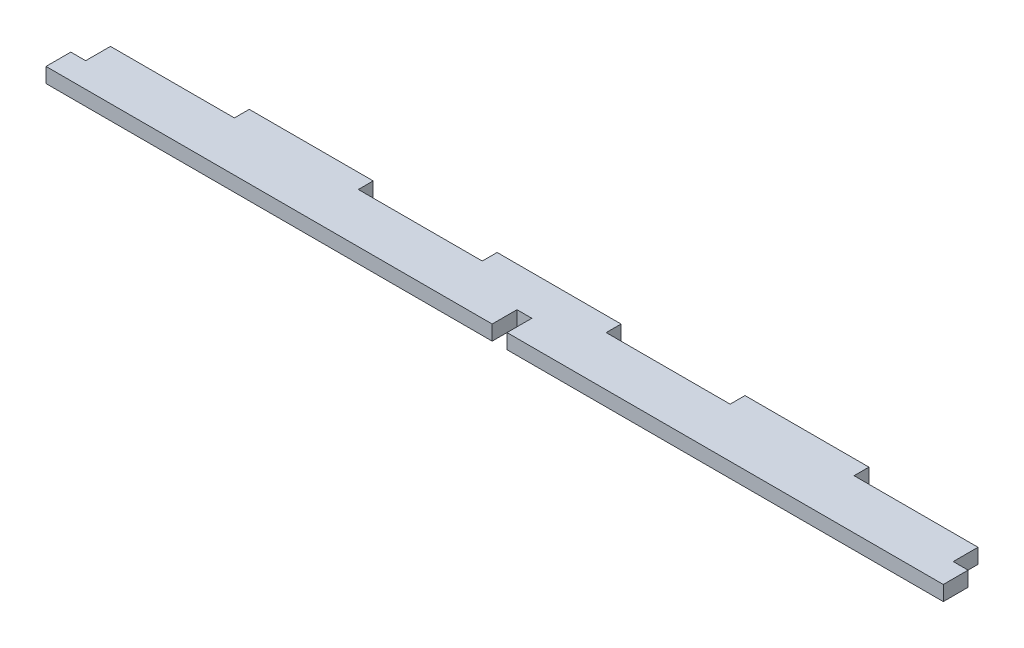
SolidWorks part; units mm, degrees
material "Buk"
ref_plane "Přední rovina" through (0, 0, 0) normal (0, 0, 1) x (1, 0, 0)
ref_plane "Horní rovina" through (0, 0, 0) normal (0, 1, 0) x (1, 0, 0)
ref_plane "Pravá rovina" through (0, 0, 0) normal (1, 0, 0) x (0, 0, -1)
sketch "Skica1" plane through (0, 0, 0) normal (0, 1, 0) x (1, 0, 0)
  line L1 (0, 10) -> (175, 10)
  line L2 (0, 10) -> (0, 0)
  line L3 (0, 0) -> (175, 0)
  line L4 (175, 10) -> (175, 0)
  dimension "D1" = 10
  dimension "D2" = 175
extrude "Přidat vysunutím1" add sketch "Skica1" along normal blind 3
sketch "Skica2" plane through (0, 0, 0) normal (0, 1, 0) x (1, 0, 0)
  line L0 (175, 10) -> (0, 10) construction
  line L1 (0, 0) -> (-3, 0)
  line L2 (0, 0) -> (0, 5)
  line L3 (0, 5) -> (-3, 5)
  line L4 (-3, 0) -> (-3, 5)
  line L5 (175, 0) -> (178, 0)
  line L6 (175, 0) -> (175, 5)
  line L7 (175, 5) -> (178, 5)
  line L8 (178, 0) -> (178, 5)
  line L9 (25, 10) -> (50, 10)
  line L10 (25, 10) -> (25, 13)
  line L11 (25, 13) -> (50, 13)
  line L12 (50, 10) -> (50, 13)
  line L14 (75, 10) -> (100, 10)
  line L15 (75, 10) -> (75, 13)
  line L16 (75, 13) -> (100, 13)
  line L17 (100, 10) -> (100, 13)
  line L18 (125, 10) -> (150, 10)
  line L19 (125, 10) -> (125, 13)
  line L20 (125, 13) -> (150, 13)
  line L21 (150, 10) -> (150, 13)
  line L22 (50, 13) -> (75, 13) construction
  line L23 (0, 10) -> (25, 10) construction
  dimension "D1" = 5
  dimension "D2" = 3
  dimension "D4" = 25
  dimension "D5" = 3
extrude "Přidat vysunutím2" add sketch "Skica2" along normal up to surface (3 mm away) up to face at (87.5, 3, -5)
sketch "Skica3" plane through (0, 0, 0) normal (0, 1, 0) x (1, 0, 0)
  line L0 (-3, 0) -> (178, 0) construction
  line L1 (87, 0) -> (90, 0)
  line L2 (87, 0) -> (87, 5)
  line L3 (87, 5) -> (90, 5)
  line L4 (90, 0) -> (90, 5)
  line L7 (175, 5) -> (175, 10) construction
  line L8 (100, 10) -> (100, 13) construction
  line L9 (-3, 5) -> (-3, 0) construction
  dimension "D1" = 85
extrude "Odebrat vysunutím1" cut sketch "Skica3" along normal through all
sketch "Skica4" plane through (0, 3, 0) normal (0, 1, 0) x (1, 0, 0)
  line L0 (28.67, 13) -> (28.67, 10) construction
  line L1 (28.67, 13) -> (28.67, 10)
  line L2 (28.67, 10) -> (50, 10)
  line L3 (50, 10) -> (50, 13)
  line L4 (50, 13) -> (28.67, 13)
  line L5 (75, 13) -> (75, 10) construction
  line L6 (83.12, 10) -> (75, 10)
  line L7 (83.12, 10) -> (83.12, 13)
  line L8 (83.12, 13) -> (75, 13)
  line L9 (75, 10) -> (75, 13)
  line L10 (100, 13) -> (75, 13) construction
extrude "Odebrat vysunutím2" [suppressed] cut sketch "Skica4" against normal through all
